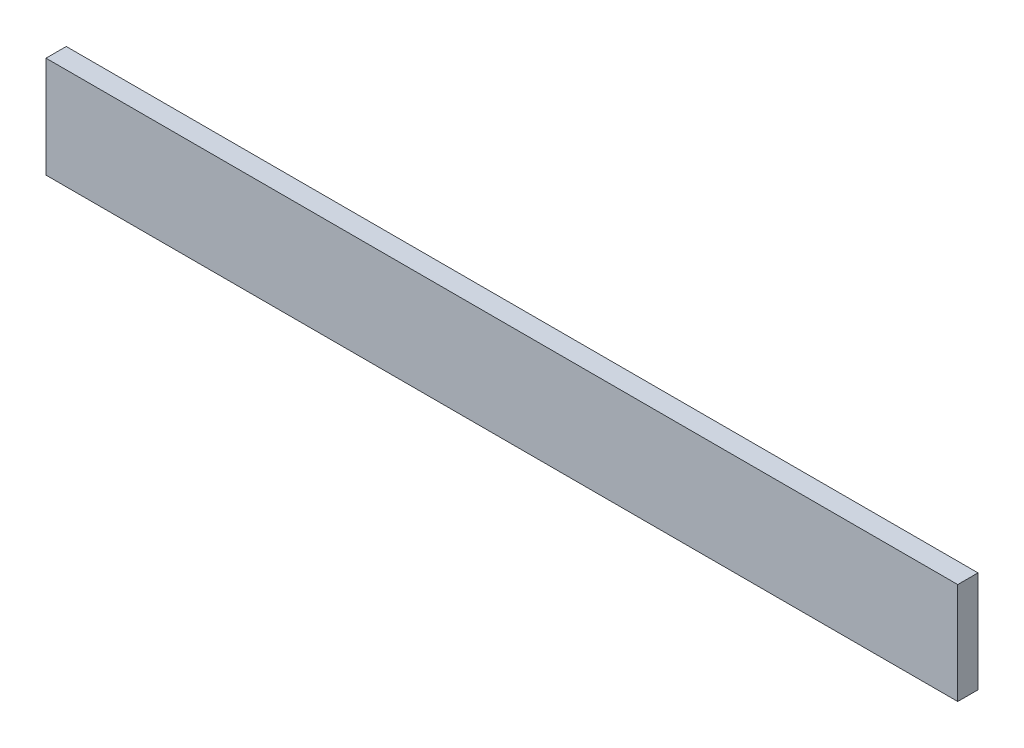
SolidWorks part; units mm, degrees
ref_plane "Front Plane" through (0, 0, 0) normal (0, 0, 1) x (1, 0, 0)
ref_plane "Top Plane" through (0, 0, 0) normal (0, 1, 0) x (1, 0, 0)
ref_plane "Right Plane" through (0, 0, 0) normal (1, 0, 0) x (0, 0, -1)
sketch "Sketch1" plane through (0, 0, 0) normal (0, 0, 1) x (1, 0, 0)
  line L1 (-450, 50) -> (450, 50)
  line L2 (-450, 50) -> (-450, -50)
  line L3 (-450, -50) -> (450, -50)
  line L4 (450, 50) -> (450, -50)
  line L5 (-450, 50) -> (450, -50) construction
  line L6 (-450, -50) -> (450, 50) construction
  point P0 (0, 0)
  dimension "D1" = 900
  dimension "D2" = 100
extrude "Boss-Extrude1" add sketch "Sketch1" along normal blind 20
sketch "Sketch2" plane through (0, 0, 0) normal (0, 0, 1) x (1, 0, 0)
  line L0 (450, -50) -> (450, 50) construction
  line L1 (-450, -50) -> (450, -50) construction
  circle A0 centre (0, -30.95) radius 4.826
  circle A1 centre (-300, -30.95) radius 4.826
  circle A2 centre (300, -30.95) radius 4.826
  circle A3 centre (-300, -30.95) radius 9.7
  circle A4 centre (0, -30.95) radius 9.7
  circle A5 centre (300, -30.95) radius 9.7
  dimension "D1" = 450
  dimension "D2" = 300
  dimension "D3" = 300
  dimension "D4" = 9.652
  dimension "D5" = 9.652
  dimension "D6" = 9.652
  dimension "D7" = 19.05
  dimension "D8" = 19.05
  dimension "D9" = 19.05
  dimension "D10" = 19.4
  dimension "D11" = 19.4
  dimension "D12" = 19.4
extrude "Boss-Extrude2" add sketch "Sketch2" against normal blind 15.8
